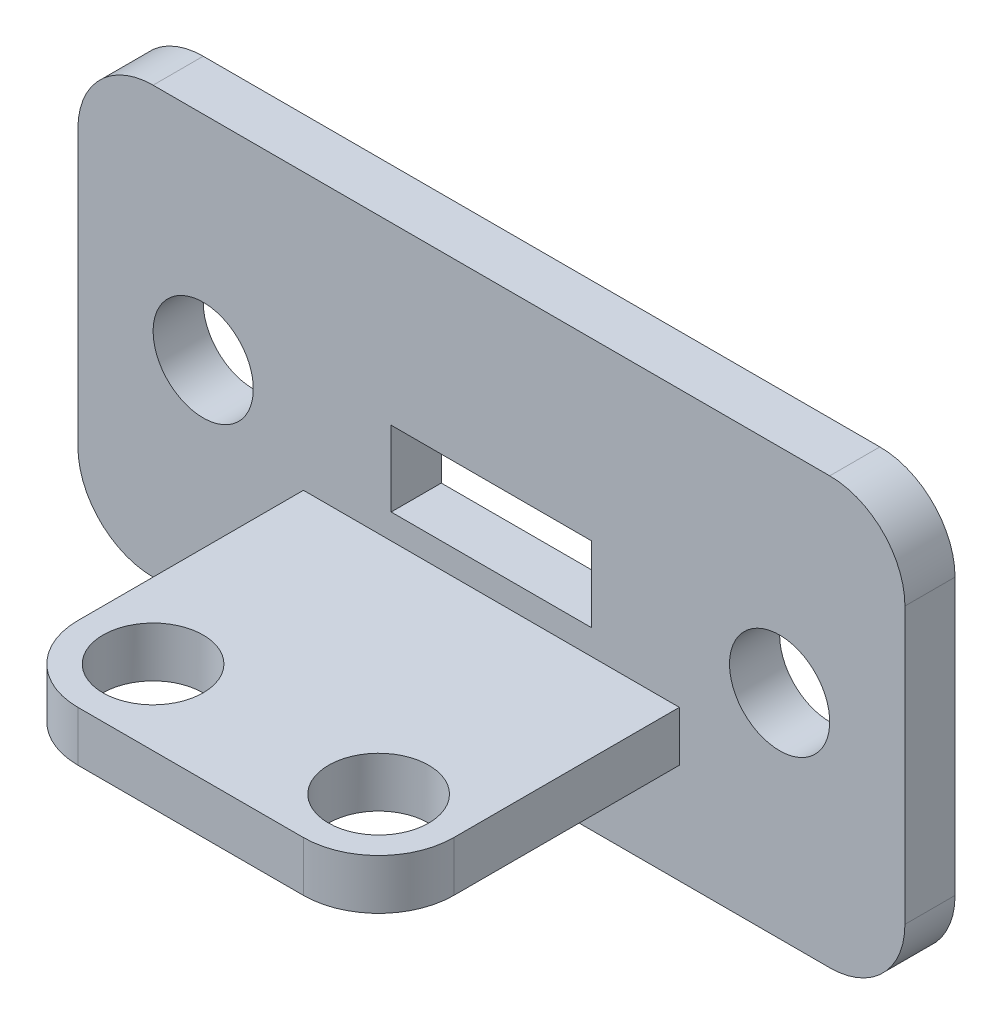
SolidWorks part; units mm, degrees
ref_plane "Alzado" through (0, 0, 0) normal (0, 0, 1) x (1, 0, 0)
ref_plane "Planta" through (0, 0, 0) normal (0, 1, 0) x (1, 0, 0)
ref_plane "Vista lateral" through (0, 0, 0) normal (1, 0, 0) x (0, 0, -1)
sketch "Croquis1" plane through (0, 0, 0) normal (0, 1, 0) x (1, 0, 0)
  line L1 (-7.5, -6) -> (7.5, -6)
  line L2 (-7.5, -6) -> (-7.5, 6)
  line L3 (-7.5, 6) -> (7.5, 6)
  line L4 (7.5, -6) -> (7.5, 6)
  line L5 (-7.5, -6) -> (7.5, 6) construction
  line L6 (-7.5, 6) -> (7.5, -6) construction
  point P0 (0, 0)
  dimension "D1" = 12
  dimension "D2" = 15
extrude "Saliente-Extruir1" add sketch "Croquis1" along normal blind 2
sketch "Croquis2" plane through (0, 2, 0) normal (0, 1, 0) x (1, 0, 0)
  line L0 (-2.5, -3) -> (2.5, -3) construction
  line L1 (0, -3) -> (0, -6) construction
  line L2 (-7.5, -6) -> (7.5, -6) construction
  line L3 (7.5, 6) -> (-7.5, 6) construction
  circle A0 centre (-4.5, -3) radius 2
  circle A1 centre (4.5, -3) radius 2
  dimension "D2" = 4
  dimension "D1" = 5
  dimension "D3" = 9
extrude "Cortar-Extruir1" cut sketch "Croquis2" against normal up to next
sketch "Croquis3" plane through (0, 0, -6) normal (0, 0, -1) x (-1, 0, 0)
  line L0 (0, 3) -> (0, 6) construction
  line L6 (-16.5, 13) -> (16.5, 13)
  line L7 (-16.5, 13) -> (-16.5, -4)
  line L8 (-16.5, -4) -> (16.5, -4)
  line L9 (16.5, 13) -> (16.5, -4)
  line L11 (7.5, 2) -> (7.5, 0) construction
  line L13 (0, 2) -> (0, 3) construction
  line L15 (-7.5, 2) -> (7.5, 2) construction
  point P9 (0, 13)
  dimension "D3" = 9
  dimension "D1" = 3
  dimension "D4" = 1
  dimension "D2" = 7
  dimension "D5" = 7
extrude "Saliente-Extruir2" add sketch "Croquis3" along normal blind 2
sketch "Croquis5" plane through (0, 0, -6) normal (0, 0, 1) x (1, 0, 0)
  line L0 (7.5, 2) -> (-7.5, 2) construction
  line L1 (-4, 3) -> (4, 3)
  line L2 (-4, 3) -> (-4, 6)
  line L3 (-4, 6) -> (4, 6)
  line L4 (4, 3) -> (4, 6)
  line L5 (-4, 3) -> (4, 6) construction
  line L6 (-4, 6) -> (4, 3) construction
  point P0 (0, 4.5)
  point P8 (0, 2)
  dimension "D1" = 3
  dimension "D2" = 8
  dimension "D3" = 1
extrude "Cortar-Extruir3" cut sketch "Croquis5" against normal up to next
sketch "Croquis6" plane through (0, 0, -8) normal (0, 0, -1) x (-1, 0, 0)
  line L0 (-4, 3) -> (-4, 6) construction
  line L1 (-16.5, 13) -> (-16.5, -4) construction
  line L2 (16.5, -4) -> (16.5, 13) construction
  circle A0 centre (-11.5, 4.5) radius 2
  circle A1 centre (11.5, 4.5) radius 2
  point P8 (-4, 4.5)
  dimension "D1" = 4
  dimension "D2" = 5
  dimension "D3" = 5
extrude "Cortar-Extruir4" cut sketch "Croquis6" against normal up to next
fillet "Redondeo1" radius 3 4 edges at (16.5, -4, -7) (-16.5, -4, -7) (-16.5, 13, -7) (16.5, 13, -7)
fillet "Redondeo2" radius 3 2 edges at (-7.5, 1, 6) (7.5, 1, 6)
equation "\"D1@Croquis3\"=\"D1@Croquis5\""
equation "\"D4@Croquis3\"=\"D3@Croquis5\""
equation "\"D3@Croquis6\"=\"D2@Croquis6\""
equation "\"D5@Croquis3\"=\"D2@Croquis3\""
